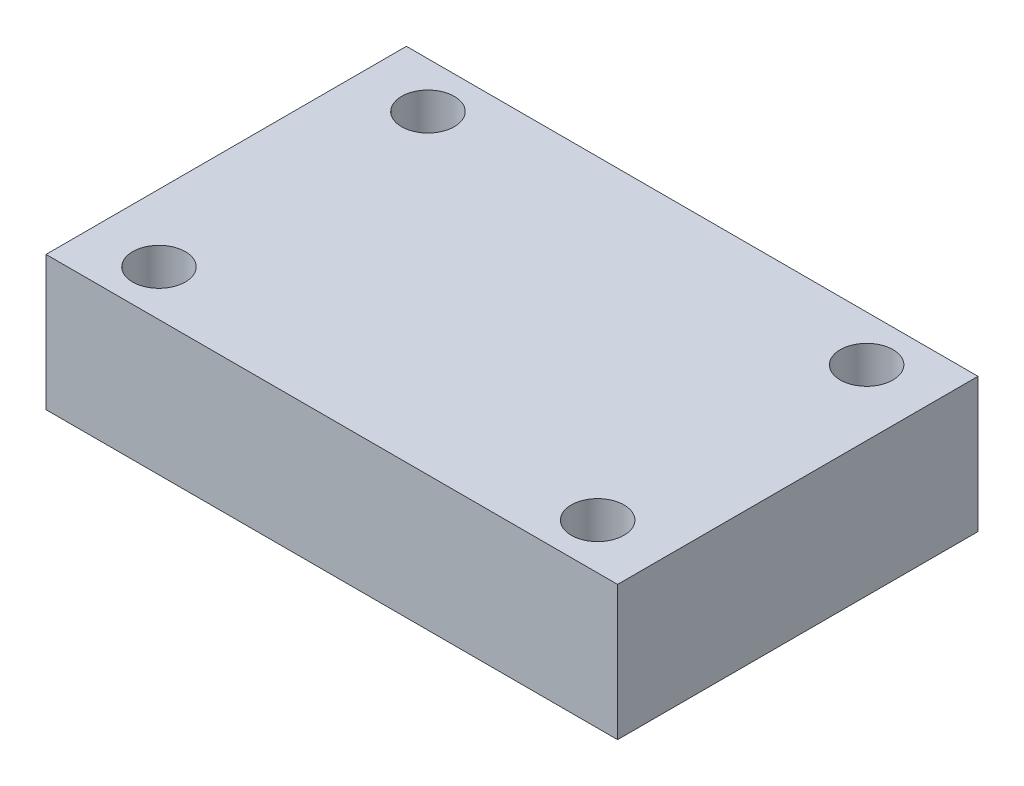
SolidWorks part; units mm, degrees
ref_plane "Front Plane" through (0, 0, 0) normal (0, 0, 1) x (1, 0, 0)
ref_plane "Top Plane" through (0, 0, 0) normal (0, 1, 0) x (1, 0, 0)
ref_plane "Right Plane" through (0, 0, 0) normal (1, 0, 0) x (0, 0, -1)
sketch "Sketch1" plane through (0, 0, 0) normal (0, 1, 0) x (1, 0, 0)
  line L0 (-26.9875, 0) -> (26.9875, 0) construction
  line L1 (0, -17.018) -> (0, 17.018) construction
  line L7 (-26.9875, 17.018) -> (26.9875, 17.018)
  line L8 (-26.9875, 17.018) -> (-26.9875, -17.018)
  line L9 (-26.9875, -17.018) -> (26.9875, -17.018)
  line L10 (26.9875, 17.018) -> (26.9875, -17.018)
  line L11 (-26.9875, 17.018) -> (26.9875, -17.018) construction
  line L12 (-26.9875, -17.018) -> (26.9875, 17.018) construction
  point P0 (0, 0)
  dimension "D1" = 53.975
  dimension "D2" = 34.036
extrude "Boss-Extrude1" add sketch "Sketch1" along normal blind 12.7
sketch "Sketch2" plane through (0, 12.7, 0) normal (0, 1, 0) x (1, 0, 0)
  line L0 (-26.9875, 17.018) -> (-20.6375, 17.018) construction
  line L1 (26.9875, 17.018) -> (-26.9875, 17.018) construction
  line L2 (-20.6375, 17.018) -> (-20.6375, 12.7) construction
  line L4 (-20.6375, 12.7) -> (20.7899, 12.7) construction
  line L5 (-20.6375, 12.7) -> (-20.6375, -12.7) construction
  line L6 (-20.6375, -12.7) -> (20.7899, -12.7) construction
  line L7 (20.7899, 12.7) -> (20.7899, -12.7) construction
  dimension "D1" = 6.35
  dimension "D2" = 4.318
  dimension "D3" = 25.4
hole_wizard "#10 Clearance Hole1" positions "Sketch3" profile "Sketch4" hole size "#10" standard "ANSI Inch" end condition through all
sketch "Sketch3" plane through (0, 12.7, 0) normal (0, 1, 0) x (1, 0, 0)
  point P0 (-20.6375, 12.7)
  point P3 (-20.6375, -12.7)
  point P6 (20.7899, -12.7)
  point P9 (20.7899, 12.7)
sketch "Sketch4" plane through (-20.6375, 12.7, -12.7) normal (1, 0, 0) x (0, 0, 1)
  line L0 (0, 0) -> (0, 12.7)
  line L1 (0, 12.7) -> (2.4892, 12.7)
  line L2 (2.4892, 12.7) -> (2.4892, 0)
  line L5 (2.4892, 0) -> (0, 0)
  line L11 (0, -6.35) -> (0, 107.95) construction
  dimension "Thru Hole Dia." = 4.9784
  dimension "Thru Hole Depth" = 12.7
